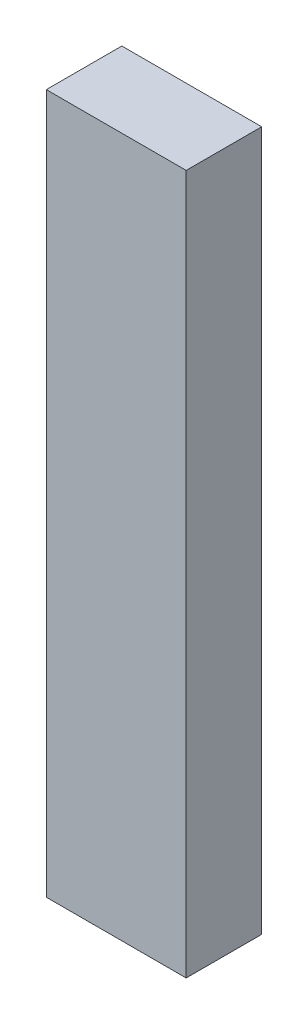
SolidWorks part; units mm, degrees
ref_plane "Front Plane" through (0, 0, 0) normal (0, 0, 1) x (1, 0, 0)
ref_plane "Top Plane" through (0, 0, 0) normal (0, 1, 0) x (1, 0, 0)
ref_plane "Right Plane" through (0, 0, 0) normal (1, 0, 0) x (0, 0, -1)
sketch "Sketch1" plane through (0, 0, 0) normal (0, 1, 0) x (1, 0, 0)
  line L1 (50, -27) -> (-50, -27)
  line L2 (50, -27) -> (50, 27)
  line L3 (50, 27) -> (-50, 27)
  line L4 (-50, -27) -> (-50, 27)
  line L5 (50, -27) -> (-50, 27) construction
  line L6 (50, 27) -> (-50, -27) construction
  point P0 (0, 0)
  point P6 (-50, -27)
  dimension "D1" = 100
  dimension "D2" = 54
extrude "Boss-Extrude1" add sketch "Sketch1" along normal blind 500 contours L3 L4 L1 L2
